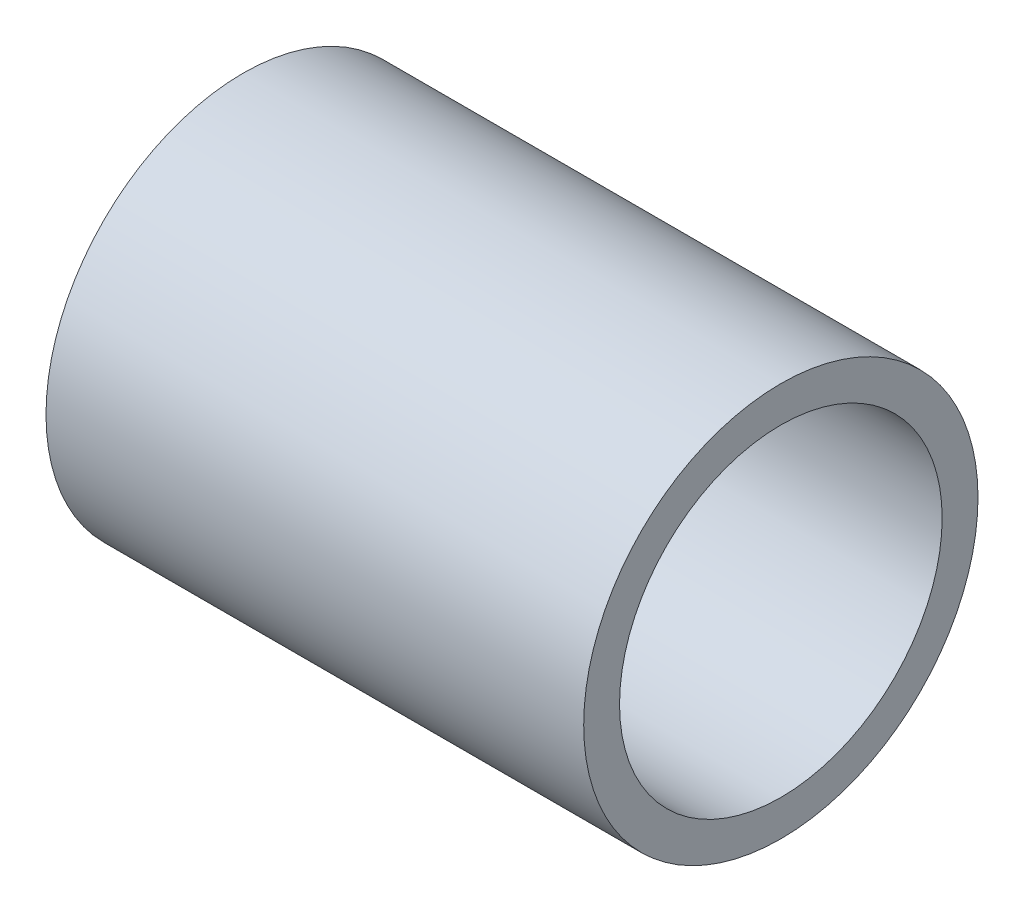
SolidWorks part; units mm, degrees
material "Plain Carbon Steel"
ref_plane "Front Plane" through (0, 0, 0) normal (0, 0, 1) x (1, 0, 0)
ref_plane "Top Plane" through (0, 0, 0) normal (0, 1, 0) x (1, 0, 0)
ref_plane "Right Plane" through (0, 0, 0) normal (1, 0, 0) x (0, 0, -1)
sketch "Sketch1" plane through (0, 0, 0) normal (1, 0, 0) x (0, 0, -1)
  circle A1 centre (0, 0) radius 11
  circle A2 centre (0, 0) radius 9
  dimension "ID" = 18
  dimension "OD" = 22
extrude "Extrude1" add sketch "Sketch1" along normal blind 30
